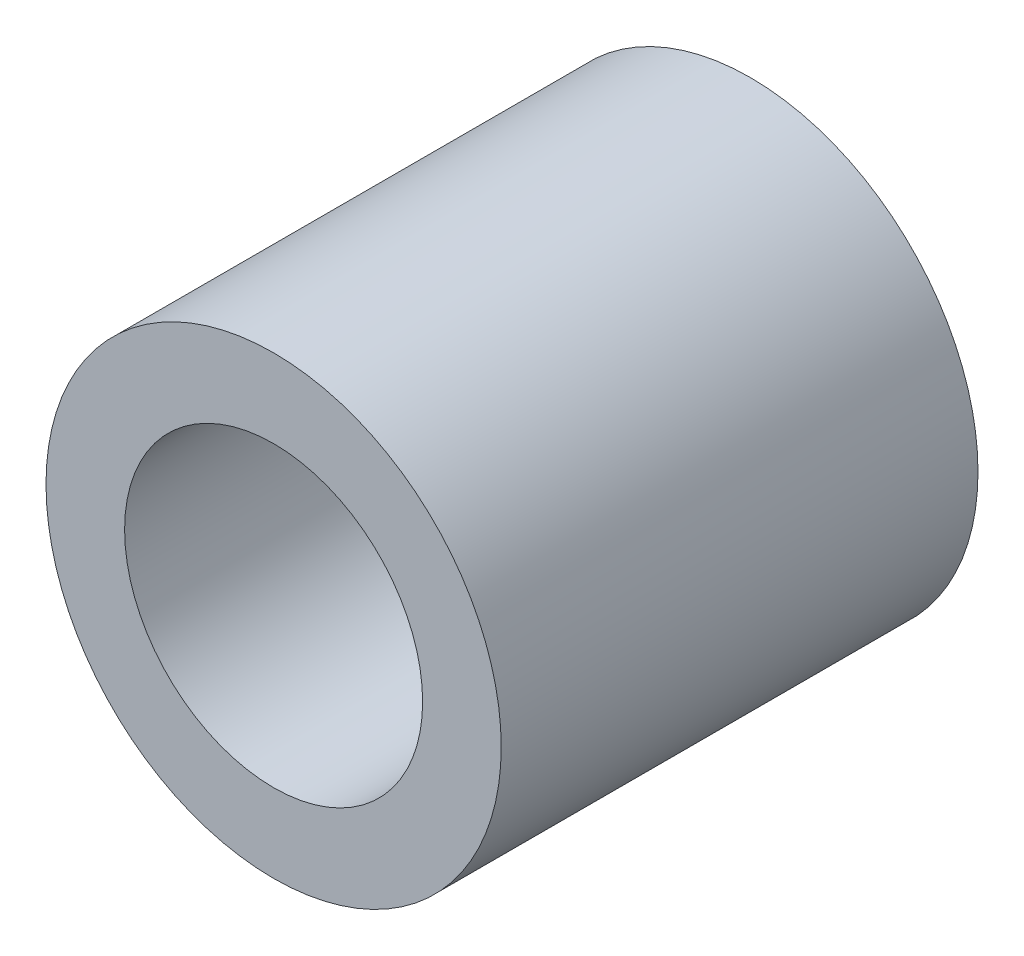
SolidWorks part; units mm, degrees
material "Nylon 101"
ref_plane "Front Plane" through (0, 0, 0) normal (0, 0, 1) x (1, 0, 0)
ref_plane "Top Plane" through (0, 0, 0) normal (0, 1, 0) x (1, 0, 0)
ref_plane "Right Plane" through (0, 0, 0) normal (1, 0, 0) x (0, 0, -1)
sketch "Sketch1" plane through (0, 0, 0) normal (0, 0, 1) x (1, 0, 0)
  circle A0 centre (0, 0) radius 7.2746
  circle A1 centre (0, 0) radius 4.7625
  dimension "D1" = 9.525
  dimension "D2" = 14.5491
extrude "Boss-Extrude1" add sketch "Sketch1" along normal mid plane 15.2375
